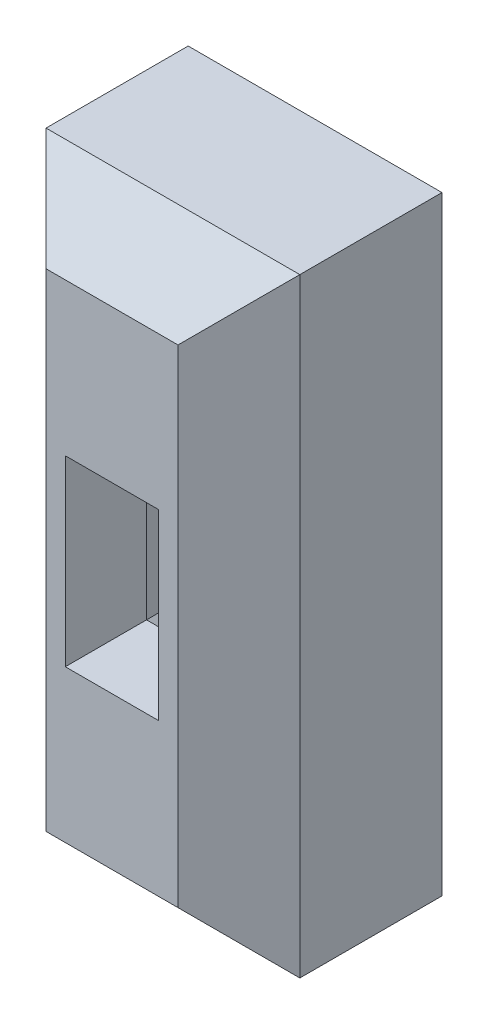
SolidWorks part; units mm, degrees
ref_plane "Plano frontal" through (0, 0, 0) normal (0, 0, 1) x (1, 0, 0)
ref_plane "Plano superior" through (0, 0, 0) normal (0, 1, 0) x (1, 0, 0)
ref_plane "Plano direito" through (0, 0, 0) normal (1, 0, 0) x (0, 0, -1)
sketch "Esboço1" plane through (0, 0, 0) normal (0, 0, 1) x (1, 0, 0)
  line L1 (-6.25, -15) -> (6.25, -15)
  line L2 (-6.25, -15) -> (-6.25, 15)
  line L3 (-6.25, 15) -> (6.25, 15)
  line L4 (6.25, -15) -> (6.25, 15)
  line L5 (-6.25, -15) -> (6.25, 15) construction
  line L6 (-6.25, 15) -> (6.25, -15) construction
  point P0 (0, 0)
  dimension "D1" = 30
  dimension "D2" = 12.5
extrude "Ressalto-extrusão1" add sketch "Esboço1" along normal blind 10
sketch "Esboço2" plane through (0, 0, 10) normal (0, 0, 1) x (1, 0, 0)
  line L1 (-2.3, -4.5) -> (2.3, -4.5)
  line L2 (-2.3, -4.5) -> (-2.3, 4.5)
  line L3 (-2.3, 4.5) -> (2.3, 4.5)
  line L4 (2.3, -4.5) -> (2.3, 4.5)
  line L5 (-2.3, -4.5) -> (2.3, 4.5) construction
  line L6 (-2.3, 4.5) -> (2.3, -4.5) construction
  point P0 (0, 0)
  dimension "D1" = 9
  dimension "D2" = 4.6
extrude "Corte-extrusão1" cut sketch "Esboço2" against normal through all
sketch "Esboço3" plane through (0, 0, 10) normal (0, 0, 1) x (1, 0, 0)
  line L1 (-2.3, 4.5) -> (-3.8, 4.5)
  line L2 (-2.3, 4.5) -> (-2.3, -4.5)
  line L3 (-2.3, -4.5) -> (-3.8, -4.5)
  line L4 (-3.8, 4.5) -> (-3.8, -4.5)
  dimension "D1" = 1.5
chamfer "Chanfro1" distance 3 angle 45 4 edges at (6.25, 0, 10) (0, -15, 10) (0, 15, 10) (-6.25, 0, 10)
chamfer "Chanfro2" distance 6 angle 25 4 edges at (2.3, 0, 0) (0, 4.5, 0) (-2.3, 0, 0) (0, -4.5, 0)
